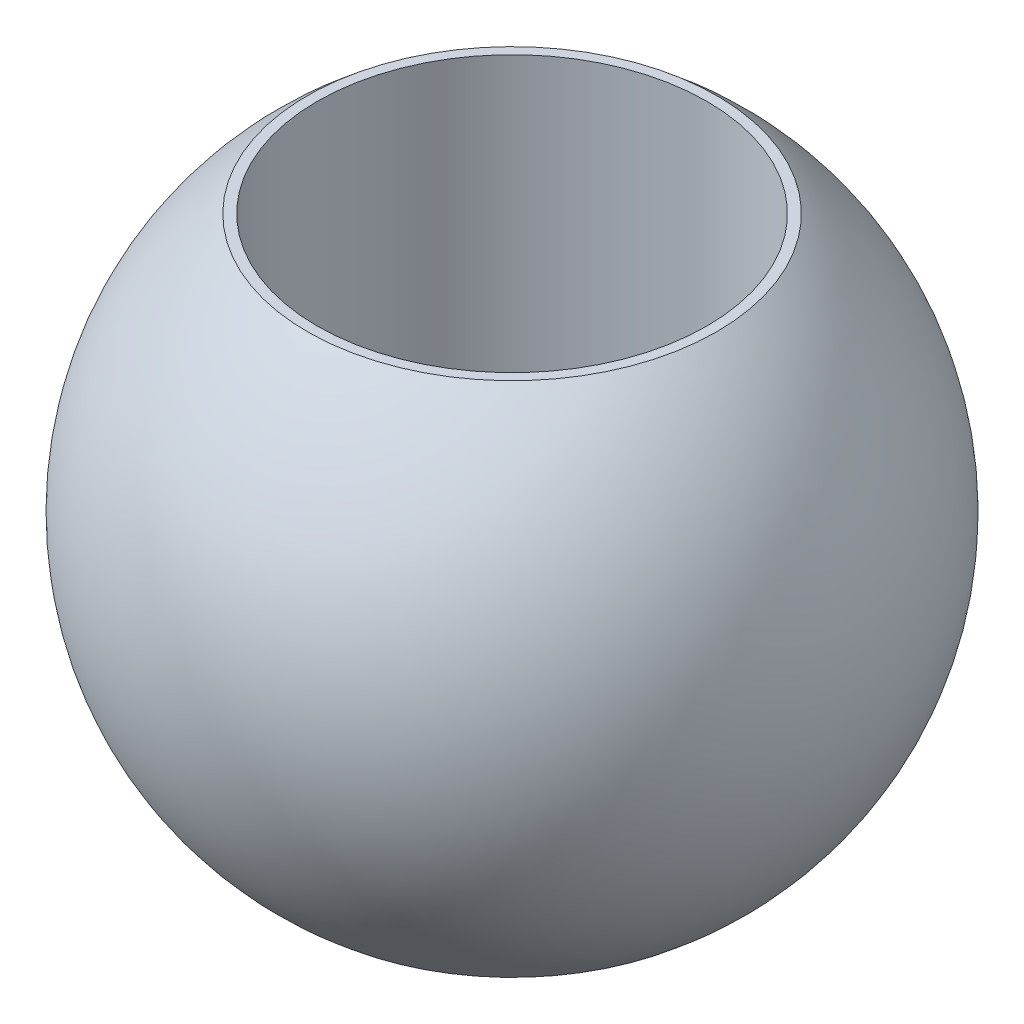
SolidWorks part; units mm, degrees
ref_plane "Front Plane" through (0, 0, 0) normal (0, 0, 1) x (1, 0, 0)
ref_plane "Top Plane" through (0, 0, 0) normal (0, 1, 0) x (1, 0, 0)
ref_plane "Right Plane" through (0, 0, 0) normal (1, 0, 0) x (0, 0, -1)
sketch "Sketch1" plane through (0, 0, 0) normal (0, 0, 1) x (1, 0, 0)
  line L0 (0, 11) -> (0, -11)
  arc A0 (0, -11) -> (0, 11) centre (0, 0) ccw
  dimension "D1" = 22
revolve "Revolve1" add sketch "Sketch1" angle 360 about L0
sketch "Sketch2" plane through (0, 0, 0) normal (0, 1, 0) x (1, 0, 0)
  circle A0 centre (0, 0) radius 6.5
  dimension "D1" = 13
extrude "Cut-Extrude1" cut sketch "Sketch2" against normal through all both and the other way through all
sketch "Sketch3" plane through (0, 0, 0) normal (0, 0, 1) x (1, 0, 0)
  line L0 (6.5, 8.8741) -> (-6.5, 8.8741) construction
  line L1 (-11.4644, 8.8741) -> (11.2891, 8.8741)
  line L2 (-11.4644, 8.8741) -> (-11.4644, 8.6241)
  line L3 (-11.4644, 8.6241) -> (11.2891, 8.6241)
  line L4 (11.2891, 8.8741) -> (11.2891, 8.6241)
  line L5 (6.5, -8.8741) -> (-6.5, -8.8741) construction
  line L6 (-12.2006, -8.6241) -> (11.7449, -8.6241)
  line L7 (-12.2006, -8.6241) -> (-12.2006, -8.8741)
  line L8 (-12.2006, -8.8741) -> (11.7449, -8.8741)
  line L9 (11.7449, -8.6241) -> (11.7449, -8.8741)
  dimension "D1" = 0.25
  dimension "D2" = 0.25
extrude "Cut-Extrude2" cut sketch "Sketch3" against normal through all both and the other way through all
